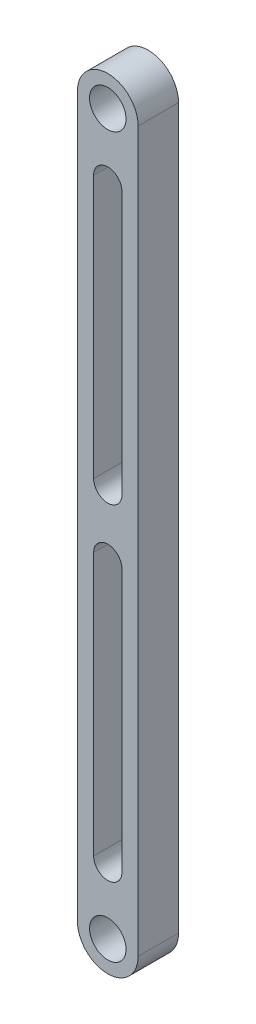
SolidWorks part; units mm, degrees
material "PEI"
ref_plane "Front Plane" through (0, 0, 0) normal (0, 0, 1) x (1, 0, 0)
ref_plane "Top Plane" through (0, 0, 0) normal (0, 1, 0) x (1, 0, 0)
ref_plane "Right Plane" through (0, 0, 0) normal (1, 0, 0) x (0, 0, -1)
sketch "Sketch1" plane through (0, 0, 0) normal (0, 0, 1) x (1, 0, 0)
  line L0 (0, -88.9) -> (0, 88.9) construction
  line L1 (-7.5, -88.9) -> (-7.5, 88.9)
  line L2 (7.5, -88.9) -> (7.5, 88.9)
  line L3 (0, -72.9) -> (0, -7.9) construction
  line L4 (-3.5, -72.9) -> (-3.5, -7.9)
  line L5 (3.5, -72.9) -> (3.5, -7.9)
  line L6 (0, 72.9) -> (0, 7.9) construction
  line L7 (3.5, 72.9) -> (3.5, 7.9)
  line L8 (-3.5, 72.9) -> (-3.5, 7.9)
  line L9 (-3.5, 40.4) -> (3.5, 40.4) construction
  line L10 (-3.5, -40.4) -> (3.5, -40.4) construction
  line L11 (-4.515, -88.9) -> (-3.5, -72.9) construction
  line L12 (-4.515, 88.9) -> (-3.5, 72.9) construction
  arc A0 (-7.5, -88.9) -> (7.5, -88.9) centre (0, -88.9) ccw
  arc A1 (7.5, 88.9) -> (-7.5, 88.9) centre (0, 88.9) ccw
  circle A2 centre (0, -88.9) radius 4.515
  circle A3 centre (0, 88.9) radius 4.515
  arc A4 (-3.5, -72.9) -> (3.5, -72.9) centre (0, -72.9) ccw
  arc A5 (3.5, -7.9) -> (-3.5, -7.9) centre (0, -7.9) ccw
  arc A6 (3.5, 72.9) -> (-3.5, 72.9) centre (0, 72.9) ccw
  arc A7 (-3.5, 7.9) -> (3.5, 7.9) centre (0, 7.9) ccw
  point P2 (0, 0)
  point P14 (0, -40.4)
  point P19 (0, 40.4)
  dimension "D3" = 9.03
  dimension "D1" = 177.8
  dimension "D2" = 15
  dimension "D4" = 7
  dimension "60" = 65
  dimension "D6" = 16
extrude "Boss-Extrude1" add sketch "Sketch1" along normal blind 10
